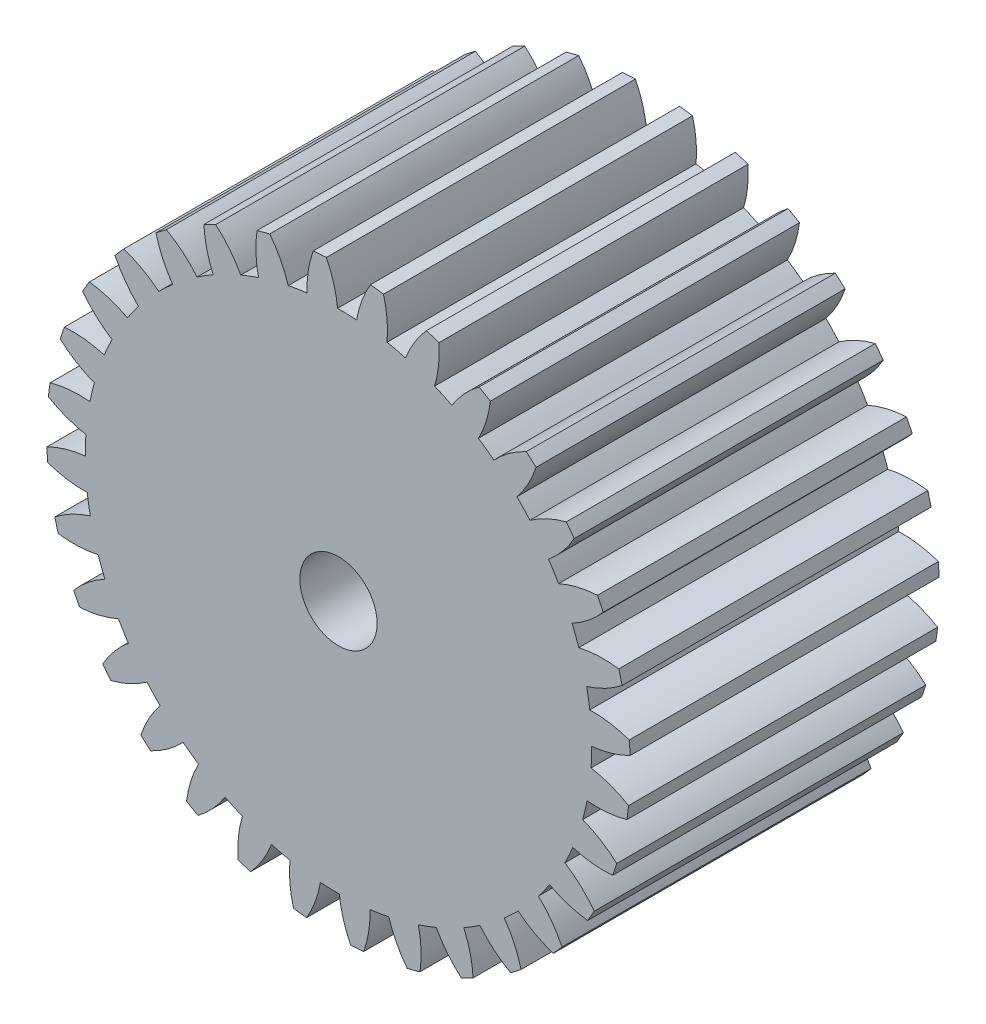
SolidWorks part; units mm, degrees
ref_plane "Front Plane" through (0, 0, 0) normal (0, 0, 1) x (1, 0, 0)
ref_plane "Top Plane" through (0, 0, 0) normal (0, 1, 0) x (1, 0, 0)
ref_plane "Right Plane" through (0, 0, 0) normal (1, 0, 0) x (0, 0, -1)
sketch "Sketch1" plane through (0, 0, 0) normal (0, 0, 1) x (1, 0, 0)
  circle A0 centre (0, 0) radius 2.25
  arc A338 (14.4554, 2.9284) -> (16.521, 4.0073) centre (12.5747, 9.0458) ccw
  arc A339 (16.521, 4.0073) -> (16.3239, 4.7467) centre (0, 0) ccw
  arc A340 (16.3239, 4.7467) -> (13.9953, 4.6545) centre (15.4088, -1.5875) ccw
  arc A341 (13.9953, 4.6545) -> (13.6063, 5.6922) centre (0, 0) ccw
  arc A342 (13.6063, 5.6922) -> (15.4217, 7.1533) centre (10.5684, 11.3252) ccw
  arc A343 (15.4217, 7.1533) -> (15.0842, 7.8402) centre (0, 0) ccw
  arc A344 (15.0842, 7.8402) -> (12.8184, 7.2954) centre (15.4224, 1.4491) ccw
  arc A345 (12.8184, 7.2954) -> (12.2344, 8.2373) centre (0, 0) ccw
  arc A346 (12.2344, 8.2373) -> (13.7299, 10.0245) centre (8.1559, 13.1694) ccw
  arc A347 (13.7299, 10.0245) -> (13.2648, 10.6323) centre (0, 0) ccw
  arc A348 (13.2648, 10.6323) -> (11.1488, 9.6559) centre (14.8434, 4.43) ccw
  arc A349 (11.1488, 9.6559) -> (10.3923, 10.4658) centre (0, 0) ccw
  arc A350 (10.3923, 10.4658) -> (11.5104, 12.5105) centre (5.4299, 14.5075) ccw
  arc A351 (11.5104, 12.5105) -> (10.9356, 13.0158) centre (0, 0) ccw
  arc A352 (10.9356, 13.0158) -> (9.0508, 11.6454) centre (13.6939, 7.2407) ccw
  arc A353 (9.0508, 11.6454) -> (8.1508, 12.2922) centre (0, 0) ccw
  arc A354 (8.1508, 12.2922) -> (8.8485, 14.5156) centre (2.4953, 15.2881) ccw
  arc A355 (8.8485, 14.5156) -> (8.1863, 14.8992) centre (0, 0) ccw
  arc A356 (8.1863, 14.8992) -> (6.605, 13.1874) centre (12.0182, 9.7731) ccw
  arc A357 (6.605, 13.1874) -> (5.5961, 13.6461) centre (0, 0) ccw
  arc A358 (5.5961, 13.6461) -> (5.8466, 15.963) centre (-0.5352, 15.4811) ccw
  arc A359 (5.8466, 15.963) -> (5.1223, 16.2099) centre (0, 0) ccw
  arc A360 (5.1223, 16.2099) -> (3.9053, 14.2226) centre (9.8806, 11.93) ccw
  arc A361 (3.9053, 14.2226) -> (2.8264, 14.4757) centre (0, 0) ccw
  arc A362 (2.8264, 14.4757) -> (2.6201, 16.7969) centre (-3.5451, 15.0792) ccw
  arc A363 (2.6201, 16.7969) -> (1.8615, 16.8978) centre (0, 0) ccw
  arc A364 (1.8615, 16.8978) -> (1.0556, 14.7112) centre (7.3634, 13.6284) ccw
  arc A365 (1.0556, 14.7112) -> (-0.052, 14.7489) centre (0, 0) ccw
  arc A366 (-0.052, 14.7489) -> (-0.7072, 16.9853) centre (-6.4188, 14.0979) ccw
  arc A367 (-0.7072, 16.9853) -> (-1.4709, 16.9362) centre (0, 0) ccw
  arc A368 (-1.4709, 16.9362) -> (-1.8347, 14.6344) centre (4.5631, 14.803) ccw
  arc A369 (-1.8347, 14.6344) -> (-2.9284, 14.4554) centre (0, 0) ccw
  arc A370 (-2.9284, 14.4554) -> (-4.0073, 16.521) centre (-9.0458, 12.5747) ccw
  arc A371 (-4.0073, 16.521) -> (-4.7467, 16.3239) centre (0, 0) ccw
  arc A372 (-4.7467, 16.3239) -> (-4.6545, 13.9953) centre (1.5875, 15.4088) ccw
  arc A373 (-4.6545, 13.9953) -> (-5.6922, 13.6063) centre (0, 0) ccw
  arc A374 (-5.6922, 13.6063) -> (-7.1533, 15.4217) centre (-11.3252, 10.5684) ccw
  arc A375 (-7.1533, 15.4217) -> (-7.8402, 15.0842) centre (0, 0) ccw
  arc A376 (-7.8402, 15.0842) -> (-7.2954, 12.8184) centre (-1.4491, 15.4224) ccw
  arc A377 (-7.2954, 12.8184) -> (-8.2373, 12.2344) centre (0, 0) ccw
  arc A378 (-8.2373, 12.2344) -> (-10.0245, 13.7299) centre (-13.1694, 8.1559) ccw
  arc A379 (-10.0245, 13.7299) -> (-10.6323, 13.2648) centre (0, 0) ccw
  arc A380 (-10.6323, 13.2648) -> (-9.6559, 11.1488) centre (-4.43, 14.8434) ccw
  arc A381 (-9.6559, 11.1488) -> (-10.4658, 10.3923) centre (0, 0) ccw
  arc A382 (-10.4658, 10.3923) -> (-12.5105, 11.5104) centre (-14.5075, 5.4299) ccw
  arc A383 (-12.5105, 11.5104) -> (-13.0158, 10.9356) centre (0, 0) ccw
  arc A384 (-13.0158, 10.9356) -> (-11.6454, 9.0508) centre (-7.2407, 13.6939) ccw
  arc A385 (-11.6454, 9.0508) -> (-12.2922, 8.1508) centre (0, 0) ccw
  arc A386 (-12.2922, 8.1508) -> (-14.5156, 8.8485) centre (-15.2881, 2.4953) ccw
  arc A387 (-14.5156, 8.8485) -> (-14.8992, 8.1863) centre (0, 0) ccw
  arc A388 (-14.8992, 8.1863) -> (-13.1874, 6.605) centre (-9.7731, 12.0182) ccw
  arc A389 (-13.1874, 6.605) -> (-13.6461, 5.5961) centre (0, 0) ccw
  arc A390 (-13.6461, 5.5961) -> (-15.963, 5.8466) centre (-15.4811, -0.5352) ccw
  arc A391 (-15.963, 5.8466) -> (-16.2099, 5.1223) centre (0, 0) ccw
  arc A392 (-16.2099, 5.1223) -> (-14.2226, 3.9053) centre (-11.93, 9.8806) ccw
  arc A393 (-14.2226, 3.9053) -> (-14.4757, 2.8264) centre (0, 0) ccw
  arc A394 (-14.4757, 2.8264) -> (-16.7969, 2.6201) centre (-15.0792, -3.5451) ccw
  arc A395 (-16.7969, 2.6201) -> (-16.8978, 1.8615) centre (0, 0) ccw
  arc A396 (-16.8978, 1.8615) -> (-14.7112, 1.0556) centre (-13.6284, 7.3634) ccw
  arc A397 (-14.7112, 1.0556) -> (-14.7489, -0.052) centre (0, 0) ccw
  arc A398 (-14.7489, -0.052) -> (-16.9853, -0.7072) centre (-14.0979, -6.4188) ccw
  arc A399 (-16.9853, -0.7072) -> (-16.9362, -1.4709) centre (0, 0) ccw
  arc A400 (-16.9362, -1.4709) -> (-14.6344, -1.8347) centre (-14.803, 4.5631) ccw
  arc A401 (-14.6344, -1.8347) -> (-14.4554, -2.9284) centre (0, 0) ccw
  arc A402 (-14.4554, -2.9284) -> (-16.521, -4.0073) centre (-12.5747, -9.0458) ccw
  arc A403 (-16.521, -4.0073) -> (-16.3239, -4.7467) centre (0, 0) ccw
  arc A404 (-16.3239, -4.7467) -> (-13.9953, -4.6545) centre (-15.4088, 1.5875) ccw
  arc A405 (-13.9953, -4.6545) -> (-13.6063, -5.6922) centre (0, 0) ccw
  arc A406 (-13.6063, -5.6922) -> (-15.4217, -7.1533) centre (-10.5684, -11.3252) ccw
  arc A407 (-15.4217, -7.1533) -> (-15.0842, -7.8402) centre (0, 0) ccw
  arc A408 (-15.0842, -7.8402) -> (-12.8184, -7.2954) centre (-15.4224, -1.4491) ccw
  arc A409 (-12.8184, -7.2954) -> (-12.2344, -8.2373) centre (0, 0) ccw
  arc A410 (-12.2344, -8.2373) -> (-13.7299, -10.0245) centre (-8.1559, -13.1694) ccw
  arc A411 (-13.7299, -10.0245) -> (-13.2648, -10.6323) centre (0, 0) ccw
  arc A412 (-13.2648, -10.6323) -> (-11.1488, -9.6559) centre (-14.8434, -4.43) ccw
  arc A413 (-11.1488, -9.6559) -> (-10.3923, -10.4658) centre (0, 0) ccw
  arc A414 (-10.3923, -10.4658) -> (-11.5104, -12.5105) centre (-5.4299, -14.5075) ccw
  arc A415 (-11.5104, -12.5105) -> (-10.9356, -13.0158) centre (0, 0) ccw
  arc A416 (-10.9356, -13.0158) -> (-9.0508, -11.6454) centre (-13.6939, -7.2407) ccw
  arc A417 (-9.0508, -11.6454) -> (-8.1508, -12.2922) centre (0, 0) ccw
  arc A418 (-8.1508, -12.2922) -> (-8.8485, -14.5156) centre (-2.4953, -15.2881) ccw
  arc A419 (-8.8485, -14.5156) -> (-8.1863, -14.8992) centre (0, 0) ccw
  arc A420 (-8.1863, -14.8992) -> (-6.605, -13.1874) centre (-12.0182, -9.7731) ccw
  arc A421 (-6.605, -13.1874) -> (-5.5961, -13.6461) centre (0, 0) ccw
  arc A422 (-5.5961, -13.6461) -> (-5.8466, -15.963) centre (0.5352, -15.4811) ccw
  arc A423 (-5.8466, -15.963) -> (-5.1223, -16.2099) centre (0, 0) ccw
  arc A424 (-5.1223, -16.2099) -> (-3.9053, -14.2226) centre (-9.8806, -11.93) ccw
  arc A425 (-3.9053, -14.2226) -> (-2.8264, -14.4757) centre (0, 0) ccw
  arc A426 (-2.8264, -14.4757) -> (-2.6201, -16.7969) centre (3.5451, -15.0792) ccw
  arc A427 (-2.6201, -16.7969) -> (-1.8615, -16.8978) centre (0, 0) ccw
  arc A428 (-1.8615, -16.8978) -> (-1.0556, -14.7112) centre (-7.3634, -13.6284) ccw
  arc A429 (-1.0556, -14.7112) -> (0.052, -14.7489) centre (0, 0) ccw
  arc A430 (0.052, -14.7489) -> (0.7072, -16.9853) centre (6.4188, -14.0979) ccw
  arc A431 (0.7072, -16.9853) -> (1.4709, -16.9362) centre (0, 0) ccw
  arc A432 (1.4709, -16.9362) -> (1.8347, -14.6344) centre (-4.5631, -14.803) ccw
  arc A433 (1.8347, -14.6344) -> (2.9284, -14.4554) centre (0, 0) ccw
  arc A434 (2.9284, -14.4554) -> (4.0073, -16.521) centre (9.0458, -12.5747) ccw
  arc A435 (4.0073, -16.521) -> (4.7467, -16.3239) centre (0, 0) ccw
  arc A436 (4.7467, -16.3239) -> (4.6545, -13.9953) centre (-1.5875, -15.4088) ccw
  arc A437 (4.6545, -13.9953) -> (5.6922, -13.6063) centre (0, 0) ccw
  arc A438 (5.6922, -13.6063) -> (7.1533, -15.4217) centre (11.3252, -10.5684) ccw
  arc A439 (7.1533, -15.4217) -> (7.8402, -15.0842) centre (0, 0) ccw
  arc A440 (7.8402, -15.0842) -> (7.2954, -12.8184) centre (1.4491, -15.4224) ccw
  arc A441 (7.2954, -12.8184) -> (8.2373, -12.2344) centre (0, 0) ccw
  arc A442 (8.2373, -12.2344) -> (10.0245, -13.7299) centre (13.1694, -8.1559) ccw
  arc A443 (10.0245, -13.7299) -> (10.6323, -13.2648) centre (0, 0) ccw
  arc A444 (10.6323, -13.2648) -> (9.6559, -11.1488) centre (4.43, -14.8434) ccw
  arc A445 (9.6559, -11.1488) -> (10.4658, -10.3923) centre (0, 0) ccw
  arc A446 (10.4658, -10.3923) -> (12.5105, -11.5104) centre (14.5075, -5.4299) ccw
  arc A447 (12.5105, -11.5104) -> (13.0158, -10.9356) centre (0, 0) ccw
  arc A448 (13.0158, -10.9356) -> (11.6454, -9.0508) centre (7.2407, -13.6939) ccw
  arc A449 (11.6454, -9.0508) -> (12.2922, -8.1508) centre (0, 0) ccw
  arc A450 (12.2922, -8.1508) -> (14.5156, -8.8485) centre (15.2881, -2.4953) ccw
  arc A451 (14.5156, -8.8485) -> (14.8992, -8.1863) centre (0, 0) ccw
  arc A452 (14.8992, -8.1863) -> (13.1874, -6.605) centre (9.7731, -12.0182) ccw
  arc A453 (13.1874, -6.605) -> (13.6461, -5.5961) centre (0, 0) ccw
  arc A454 (13.6461, -5.5961) -> (15.963, -5.8466) centre (15.4811, 0.5352) ccw
  arc A455 (15.963, -5.8466) -> (16.2099, -5.1223) centre (0, 0) ccw
  arc A456 (16.2099, -5.1223) -> (14.2226, -3.9053) centre (11.93, -9.8806) ccw
  arc A457 (14.2226, -3.9053) -> (14.4757, -2.8264) centre (0, 0) ccw
  arc A458 (14.4757, -2.8264) -> (16.7969, -2.6201) centre (15.0792, 3.5451) ccw
  arc A459 (16.7969, -2.6201) -> (16.8978, -1.8615) centre (0, 0) ccw
  arc A460 (16.8978, -1.8615) -> (14.7112, -1.0556) centre (13.6284, -7.3634) ccw
  arc A461 (14.7112, -1.0556) -> (14.7489, 0.052) centre (0, 0) ccw
  arc A462 (14.7489, 0.052) -> (16.9853, 0.7072) centre (14.0979, 6.4188) ccw
  arc A463 (16.9853, 0.7072) -> (16.9362, 1.4709) centre (0, 0) ccw
  arc A464 (16.9362, 1.4709) -> (14.6344, 1.8347) centre (14.803, -4.5631) ccw
  arc A465 (14.6344, 1.8347) -> (14.4554, 2.9284) centre (0, 0) ccw
extrude "Boss-Extrude1" add sketch "Sketch1" along normal blind 3 and the other way blind 15
ref_plane "Plane1" through (0, 0, -1) normal (0, 0, 1) x (1, 0, 0)
sketch "Sketch3" plane through (0, 0, -1) normal (0, 0, 1) x (1, 0, 0)
  line L12 (-3.4641, -6) -> (3.4641, -6)
  line L13 (3.4641, -6) -> (6.9282, 0)
  line L14 (6.9282, 0) -> (3.4641, 6)
  line L15 (3.4641, 6) -> (-3.4641, 6)
  line L16 (-3.4641, 6) -> (-6.9282, 0)
  line L17 (-6.9282, 0) -> (-3.4641, -6)
  circle A0 centre (0, 0) radius 2.25
extrude "Cut-Extrude1" cut sketch "Sketch3" against normal up to surface (14 mm away) up to face at (2.25, 0, -15)
